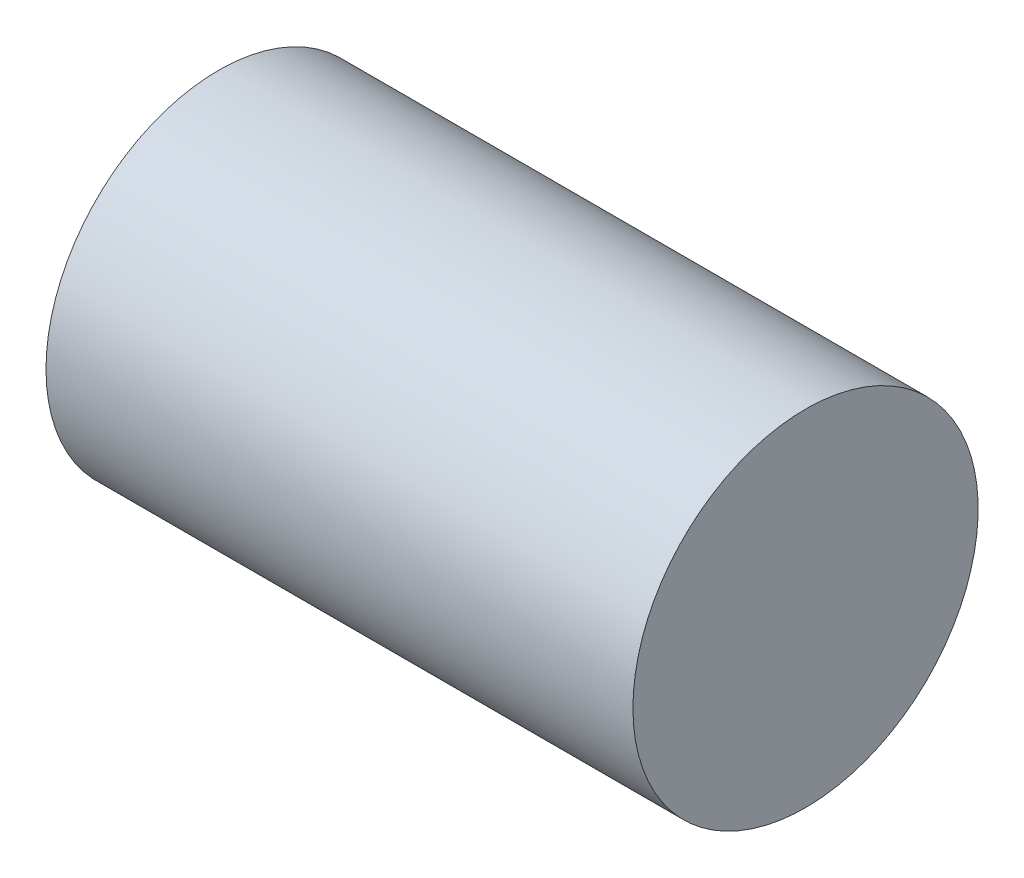
SolidWorks part; units mm, degrees
ref_plane "Front Plane" through (0, 0, 0) normal (0, 0, 1) x (1, 0, 0)
ref_plane "Top Plane" through (0, 0, 0) normal (0, 1, 0) x (1, 0, 0)
ref_plane "Right Plane" through (0, 0, 0) normal (1, 0, 0) x (0, 0, -1)
sketch "Sketch2" plane through (0, 0, 0) normal (0, 0, 1) x (1, 0, 0)
  line L0 (-9.1559, 0) -> (-5.0759, 0)
  line L1 (-5.0759, 0) -> (-5.0759, 1.2)
  line L2 (-5.0759, 1.2) -> (-9.1559, 1.2)
  line L3 (-9.1559, 1.2) -> (-9.1559, 0)
  dimension "D1" = 1.2
  dimension "D2" = 4.08
revolve "Revolve1" add sketch "Sketch2" angle 360 about L0
